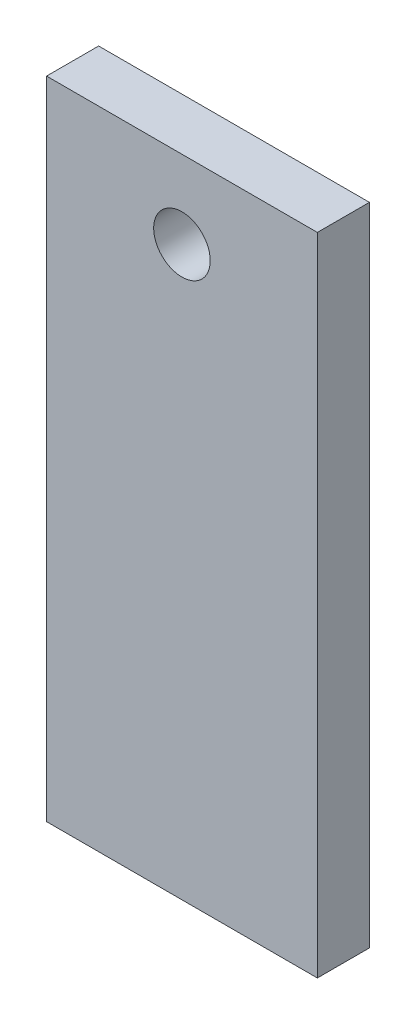
SolidWorks part; units mm, degrees
ref_plane "Plan de face" through (0, 0, 0) normal (0, 0, 1) x (1, 0, 0)
ref_plane "Plan de dessus" through (0, 0, 0) normal (0, 1, 0) x (1, 0, 0)
ref_plane "Plan de droite" through (0, 0, 0) normal (1, 0, 0) x (0, 0, -1)
sketch "Esquisse1" plane through (0, 0, 0) normal (0, 0, 1) x (1, 0, 0)
  line L2 (0, 0) -> (0, 62)
  line L4 (26, 0) -> (26, 62)
  line L6 (0, 62) -> (26, 62)
  line L10 (0, 0) -> (26, 0)
  circle A1 centre (13, 54.5) radius 2.715
  point P5 (25.6036, 95)
  point P6 (13, 12.8554)
  point P7 (0, 0)
  dimension "D10" = 5.43
  dimension "D1" = 26
  dimension "D2" = 62
  dimension "D3" = 7.5
extrude "Boss.-Extru.1" add sketch "Esquisse1" along normal blind 5
sketch "Esquisse3" plane through (0, 0, 0) normal (0, -1, 0) x (1, 0, 0)
  line L0 (3.1547, 0) -> (2, 2)
  line L3 (8.1094, 2) -> (6.9547, 0)
  line L4 (6.9547, 0) -> (3.1547, 0)
  line L5 (19.0453, 0) -> (17.8906, 2)
  line L6 (0, 0) -> (26, 0) construction
  line L8 (24, 2) -> (22.8453, 0)
  line L9 (22.8453, 0) -> (19.0453, 0)
  line L12 (2, 2) -> (2, 2.6)
  line L13 (2, 2.6) -> (8.1094, 2.6)
  line L14 (8.1094, 2) -> (8.1094, 2.6)
  line L16 (17.8906, 2) -> (17.8906, 2.6)
  line L17 (17.8906, 2.6) -> (24, 2.6)
  line L18 (24, 2) -> (24, 2.6)
  line L20 (0, 0) -> (26, 0) construction
  line L21 (26, 5) -> (26, 0) construction
  line L22 (0, 5) -> (0, 0) construction
  point P16 (0, 0)
  point P17 (0, 0)
  dimension "D2" = 60
  dimension "D3" = 60
  dimension "D4" = 3.8
  dimension "D5" = 2
  dimension "D6" = 2
  dimension "D7" = 0.6
  dimension "D8" = 0.6
  dimension "D9" = 0.6
  dimension "D10" = 0.6
  dimension "D11" = 2
  dimension "D12" = 2
extrude "Enlèv. mat.-Extru.1" cut sketch "Esquisse3" against normal blind 60.5 and the other way through all
fillet "Congé3" radius 0.3 4 edges at (19.0453, 30.25, 0) (22.8453, 30.25, 0) (6.9547, 30.25, 0) (3.1547, 30.25, 0)
